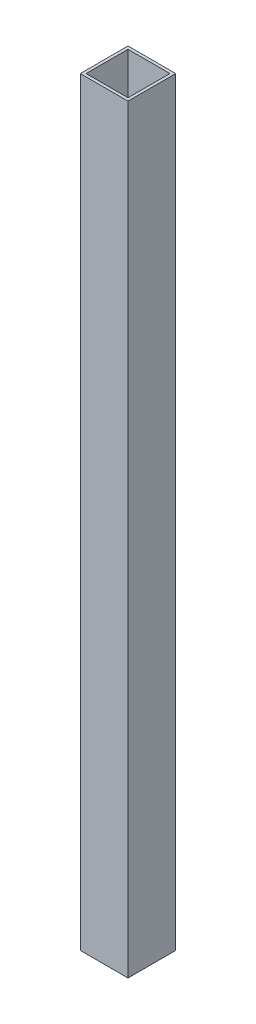
SolidWorks part; units mm, degrees
ref_plane "Front Plane" through (0, 0, 0) normal (0, 0, 1) x (1, 0, 0)
ref_plane "Top Plane" through (0, 0, 0) normal (0, 1, 0) x (1, 0, 0)
ref_plane "Right Plane" through (0, 0, 0) normal (1, 0, 0) x (0, 0, -1)
sketch "Sketch1" plane through (0, 0, 0) normal (0, 1, 0) x (1, 0, 0)
  line L1 (-12.5, -12.5) -> (12.5, -12.5)
  line L2 (-12.5, -12.5) -> (-12.5, 12.5)
  line L3 (-12.5, 12.5) -> (12.5, 12.5)
  line L4 (12.5, -12.5) -> (12.5, 12.5)
  line L5 (-12.5, -12.5) -> (12.5, 12.5) construction
  line L6 (-12.5, 12.5) -> (12.5, -12.5) construction
  point P0 (0, 0)
  dimension "D1" = 25
extrude "Extrude-Thin1" add sketch "Sketch1" along normal mid plane 398 thin thin type one direction reverse wall 1.5
